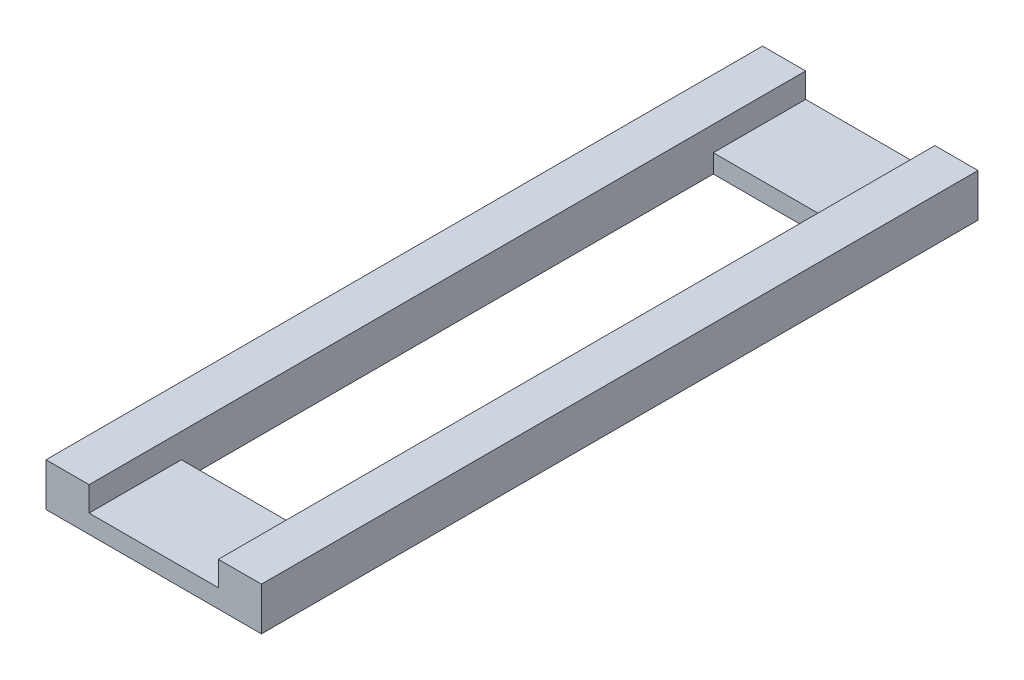
SolidWorks part; units mm, degrees
ref_plane "Alzado" through (0, 0, 0) normal (0, 0, 1) x (1, 0, 0)
ref_plane "Planta" through (0, 0, 0) normal (0, 1, 0) x (1, 0, 0)
ref_plane "Vista lateral" through (0, 0, 0) normal (1, 0, 0) x (0, 0, -1)
sketch "Croquis1" plane through (0, 0, 0) normal (0, 1, 0) x (1, 0, 0)
  line L1 (-87.5, -291) -> (87.5, -291)
  line L2 (-87.5, -291) -> (-87.5, 291)
  line L3 (-87.5, 291) -> (87.5, 291)
  line L4 (87.5, -291) -> (87.5, 291)
  line L5 (-87.5, -291) -> (87.5, 291) construction
  line L6 (-87.5, 291) -> (87.5, -291) construction
  point P0 (0, 0)
  dimension "D1" = 582
  dimension "D2" = 175
extrude "Saliente-Extruir1" add sketch "Croquis1" along normal blind 35
sketch "Croquis2" plane through (0, 35, 0) normal (0, 1, 0) x (1, 0, 0)
  line L0 (87.5, 291) -> (-87.5, 291) construction
  line L1 (52.5, -291) -> (-52.5, -291)
  line L2 (52.5, -291) -> (52.5, 291)
  line L3 (52.5, 291) -> (-52.5, 291)
  line L4 (-52.5, -291) -> (-52.5, 291)
  line L5 (52.5, -291) -> (-52.5, 291) construction
  line L6 (52.5, 291) -> (-52.5, -291) construction
  line L7 (-87.5, 291) -> (-87.5, -291) construction
  point P0 (0, 0)
  dimension "D1" = 35
extrude "Cortar-Extruir1" cut sketch "Croquis2" against normal blind 20
sketch "Croquis3" plane through (0, 15, 0) normal (0, 1, 0) x (1, 0, 0)
  line L0 (-52.5, 291) -> (-52.5, -291) construction
  line L1 (52.5, -216) -> (-52.5, -216)
  line L2 (52.5, -216) -> (52.5, 216)
  line L3 (52.5, 216) -> (-52.5, 216)
  line L4 (-52.5, -216) -> (-52.5, 216)
  line L5 (52.5, -216) -> (-52.5, 216) construction
  line L6 (52.5, 216) -> (-52.5, -216) construction
  line L7 (52.5, 291) -> (-52.5, 291) construction
  point P0 (0, 0)
  dimension "D1" = 75
extrude "Cortar-Extruir2" cut sketch "Croquis3" against normal through all
